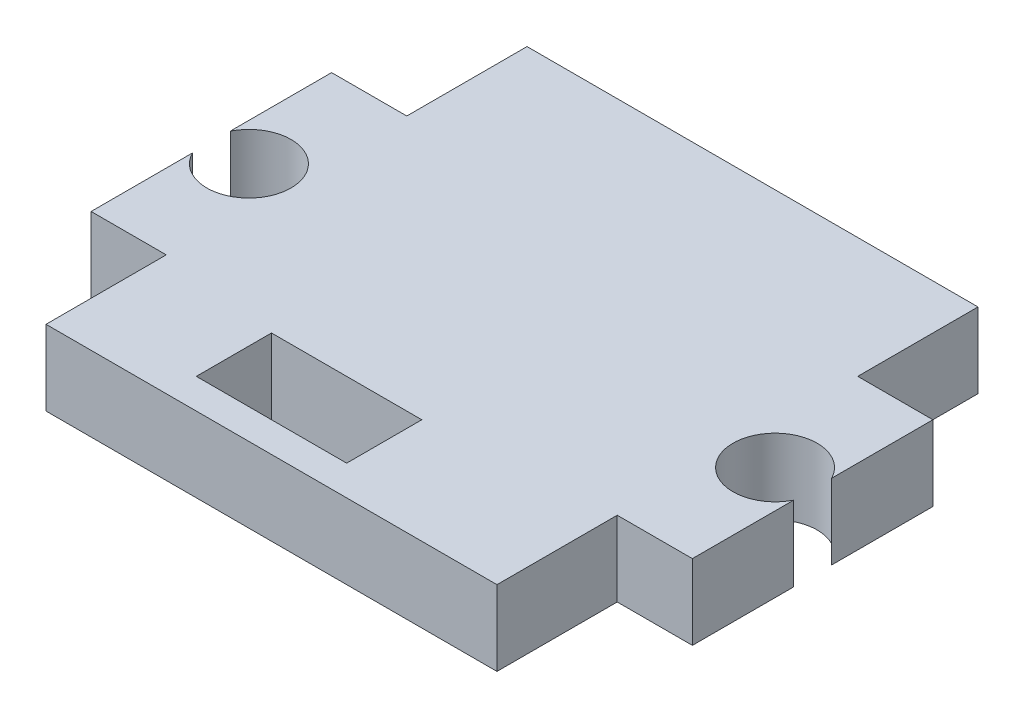
SolidWorks part; units mm, degrees
ref_plane "前视基准面" through (0, 0, 0) normal (0, 0, 1) x (1, 0, 0)
ref_plane "上视基准面" through (0, 0, 0) normal (0, 1, 0) x (1, 0, 0)
ref_plane "右视基准面" through (0, 0, 0) normal (1, 0, 0) x (0, 0, -1)
sketch "Sketch1" plane through (0, 0, 0) normal (0, 1, 0) x (1, 0, 0)
  line L1 (0, 0) -> (25.4, 0)
  line L2 (0, 0) -> (0, -20.32)
  line L3 (0, -20.32) -> (25.4, -20.32)
  line L4 (25.4, 0) -> (25.4, -20.32)
  dimension "D1" = 25.4
  dimension "D2" = 20.32
extrude "Boss-Extrude1" add sketch "Sketch1" along normal blind 3.175
sketch "Sketch2" plane through (0, 3.175, 0) normal (0, 1, 0) x (1, 0, 0)
  line L1 (0, 0) -> (3.175, 0)
  line L2 (0, 0) -> (0, -5.08)
  line L3 (0, -5.08) -> (3.175, -5.08)
  line L4 (3.175, 0) -> (3.175, -5.08)
  line L5 (0, -20.32) -> (3.175, -20.32)
  line L6 (0, -20.32) -> (0, -15.24)
  line L7 (0, -15.24) -> (3.175, -15.24)
  line L8 (3.175, -20.32) -> (3.175, -15.24)
  line L9 (25.4, 0) -> (22.225, 0)
  line L10 (25.4, 0) -> (25.4, -5.08)
  line L11 (25.4, -5.08) -> (22.225, -5.08)
  line L12 (22.225, 0) -> (22.225, -5.08)
  line L13 (25.4, -20.32) -> (22.225, -20.32)
  line L14 (25.4, -20.32) -> (25.4, -15.24)
  line L15 (25.4, -15.24) -> (22.225, -15.24)
  line L16 (22.225, -20.32) -> (22.225, -15.24)
  dimension "D1" = 5.08
  dimension "D2" = 5.08
  dimension "D3" = 3.175
  dimension "D4" = 3.175
  dimension "D5" = 3.175
  dimension "D6" = 5.08
  dimension "D7" = 5.08
extrude "Cut-Extrude1" cut sketch "Sketch2" against normal blind 3.175
sketch "Sketch3" plane through (0, 3.175, 0) normal (0, 1, 0) x (1, 0, 0)
  line L0 (0, -5.08) -> (3.175, -5.08) construction
  line L1 (0, -5.08) -> (0, -15.24) construction
  line L2 (22.225, -5.08) -> (25.4, -5.08) construction
  line L3 (25.4, -15.24) -> (25.4, -5.08) construction
  circle A0 centre (1.5875, -10.16) radius 1.778
  circle A1 centre (23.8125, -10.16) radius 1.778
  point P8 (23.8125, -5.08)
  point P13 (23.5647, -7.6456)
  dimension "D3" = 3.556
  dimension "D6" = 3.556
  dimension "D1" = 5.08
  dimension "D2" = 1.5875
  dimension "D4" = 5.08
  dimension "D5" = 1.5875
extrude "Cut-Extrude2" cut sketch "Sketch3" against normal blind 3.175
sketch "Sketch4" plane through (0, 3.175, 0) normal (0, 1, 0) x (1, 0, 0)
  line L0 (3.175, -20.32) -> (22.225, -20.32) construction
  line L1 (8.255, -15.875) -> (14.605, -15.875)
  line L2 (8.255, -15.875) -> (8.255, -19.05)
  line L3 (8.255, -19.05) -> (14.605, -19.05)
  line L4 (14.605, -15.875) -> (14.605, -19.05)
  line L5 (3.175, -20.32) -> (3.175, -15.24) construction
  dimension "D1" = 3.175
  dimension "D2" = 6.35
  dimension "D3" = 1.27
  dimension "D4" = 5.08
extrude "Cut-Extrude3" cut sketch "Sketch4" against normal blind 3.175
